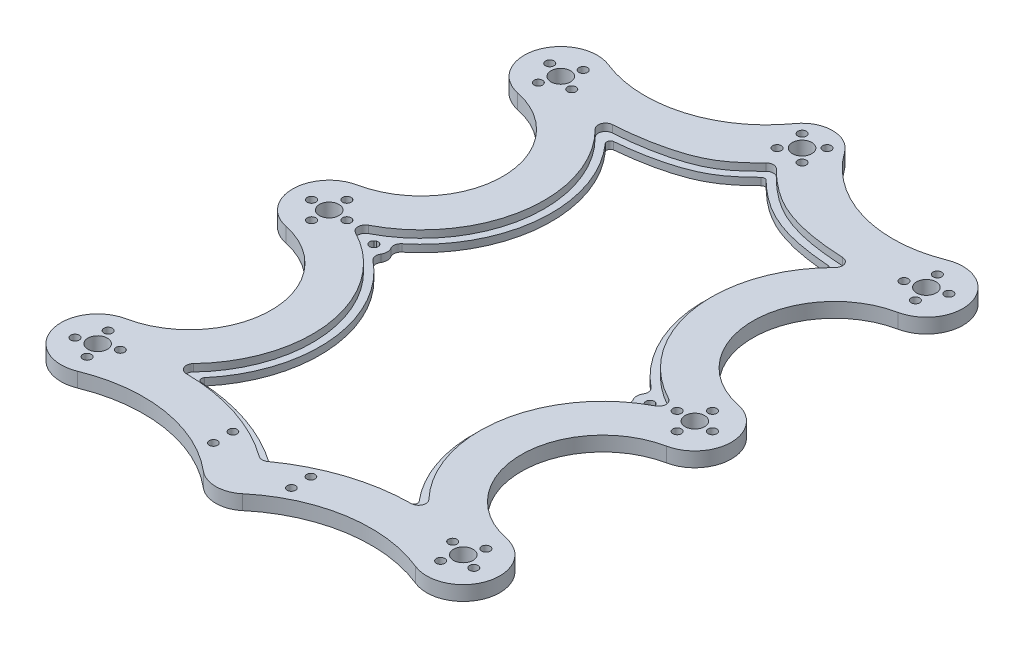
SolidWorks part; units mm, degrees
ref_plane "Front Plane" through (0, 0, 0) normal (0, 0, 1) x (1, 0, 0)
ref_plane "Top Plane" through (0, 0, 0) normal (0, 1, 0) x (1, 0, 0)
ref_plane "Right Plane" through (0, 0, 0) normal (1, 0, 0) x (0, 0, -1)
sketch "Sketch1" plane through (0, 0, 0) normal (0, 1, 0) x (1, 0, 0)
  line L0 (-75, 0) -> (75, 0) construction
  line L1 (-75, -95) -> (-75, -190) construction
  line L3 (0, 0) -> (0, -204) construction
  line L4 (0, 0) -> (0, 24)
  circle A0 centre (-75, 0) radius 15
  circle A1 centre (75, 0) radius 15
  circle A2 centre (-75, -95) radius 15
  circle A3 centre (75, -95) radius 15
  circle A4 centre (-75, -190) radius 15
  circle A5 centre (75, -190) radius 15
  circle A6 centre (-84.798, -142.5) radius 33.5
  circle A10 centre (0, -204) radius 12.5
  circle A11 centre (0, 24) radius 12.5
  circle A12 centre (-46.7001, -259.4559) radius 60
  circle A13 centre (46.7001, -259.4559) radius 60
  circle A14 centre (-50.8455, 60.3453) radius 50
  circle A15 centre (50.8455, 60.3453) radius 50
  circle A16 centre (84.798, -142.5) radius 33.5
  circle A17 centre (-84.798, -47.5) radius 33.5
  circle A18 centre (84.798, -47.5) radius 33.5
  dimension "D3" = 30
  dimension "D4" = 30
  dimension "D10" = 25
  dimension "D12" = 25
  dimension "D13" = 120
  dimension "D14" = 120
  dimension "D15" = 100
  dimension "D16" = 100
  dimension "D6" = 67
  dimension "D7" = 67
  dimension "D8" = 67
  dimension "D17" = 67
  dimension "D1" = 3
  dimension "D2" = 150
  dimension "D5" = 95
  dimension "D9" = 228
  dimension "D11" = 24
extrude "Boss-Extrude1" add sketch "Sketch1" along normal blind 6
sketch "Sketch2" plane through (0, 0, 0) normal (0, -1, 0) x (1, 0, 0)
  circle A0 centre (-75, 190) radius 4
  circle A1 centre (-75, 95) radius 4
  circle A2 centre (-75, 0) radius 4
  circle A3 centre (75, 0) radius 4
  circle A4 centre (75, 95) radius 4
  circle A5 centre (75, 190) radius 4
  circle A6 centre (0, -24) radius 4
  arc A8 (-10.1691, -31.2691) -> (10.1691, -31.2691) centre (0, -24) ccw construction
  dimension "D1" = 8
  dimension "D2" = 8
  dimension "D3" = 8
  dimension "D4" = 8
  dimension "D5" = 8
  dimension "D6" = 8
  dimension "D7" = 8
extrude "Cut-Extrude1" cut sketch "Sketch2" against normal through all
sketch "Sketch3" plane through (0, 6, 0) normal (0, 1, 0) x (1, 0, 0)
  line L0 (0, -216.5) -> (0, -189.6086) construction
  circle A0 centre (-16, -193.5) radius 1.7
  circle A1 centre (16, -193.5) radius 1.7
  circle A2 centre (-16, -201.5) radius 1.7
  circle A3 centre (16, -201.5) radius 1.7
  arc A4 (-8.0517, -213.5614) -> (8.0517, -213.5614) centre (0, -204) ccw construction
  point P15 (0, -216.5)
  dimension "D1" = 3.4
  dimension "D2" = 3.4
  dimension "D3" = 3.4
  dimension "D4" = 3.4
  dimension "D5" = 32
  dimension "D6" = 8
  dimension "D7" = 15
  dimension "D8" = 16
extrude "Cut-Extrude2" cut sketch "Sketch3" against normal up to next
sketch "Sketch4" plane through (0, 6, 0) normal (0, 1, 0) x (1, 0, 0)
  line L0 (-75, -95) -> (75, -95) construction
  line L1 (0, 0) -> (0, -6.5) construction
  circle A1 centre (0, 9.2337) radius 3
  arc A16 (48.2843, -177.3856) -> (46.1371, -182.4579) centre (46.1152, -179.458) cw
  arc A17 (-1.7513, -196.937) -> (1.7513, -196.937) centre (0, -194.5012) ccw
  arc A18 (-46.1371, -182.4579) -> (-48.2843, -177.3856) centre (-46.1152, -179.458) cw
  arc A19 (-61.5613, -92.3364) -> (-61.5613, -97.6636) centre (-60.1809, -95) ccw
  arc A20 (61.5613, -97.6636) -> (61.5613, -92.3364) centre (60.1809, -95) ccw
  arc A21 (49.1991, -11.6814) -> (47.2455, -6.5579) centre (47.0844, -9.5535) ccw
  arc A22 (2.1791, 14.2956) -> (-2.1791, 14.2956) centre (0, 12.2337) ccw
  arc A23 (-47.2455, -6.5579) -> (-49.1991, -11.6814) centre (-47.0844, -9.5535) ccw
  arc A32 (0, 16.7135) -> (55.3066, -6.506) centre (50.8455, 60.3453) ccw
  arc A33 (-55.3066, -6.506) -> (0, 16.7135) centre (-50.8455, 60.3453) ccw
  arc A34 (-67.6515, -95) -> (-55.3066, -6.506) centre (-84.798, -47.5) ccw
  arc A35 (-54.4237, -182.8442) -> (-67.6515, -95) centre (-84.798, -142.5) ccw
  arc A36 (0, -198.2341) -> (-54.4237, -182.8442) centre (-46.7001, -259.4559) ccw
  arc A37 (54.4237, -182.8442) -> (0, -198.2341) centre (46.7001, -259.4559) ccw
  arc A38 (67.6515, -95) -> (54.4237, -182.8442) centre (84.798, -142.5) ccw
  arc A39 (55.3066, -6.506) -> (67.6515, -95) centre (84.798, -47.5) ccw
  arc A40 (2.1791, 14.2956) -> (47.2455, -6.5579) centre (50.8455, 60.3453) ccw
  arc A41 (-47.2455, -6.5579) -> (-2.1791, 14.2956) centre (-50.8455, 60.3453) ccw
  arc A42 (-61.5613, -92.3364) -> (-49.1991, -11.6814) centre (-84.798, -47.5) ccw
  arc A43 (-48.2843, -177.3856) -> (-61.5613, -97.6636) centre (-84.798, -142.5) ccw
  arc A44 (-1.7513, -196.937) -> (-46.1371, -182.4579) centre (-46.7001, -259.4559) ccw
  arc A45 (46.1371, -182.4579) -> (1.7513, -196.937) centre (46.7001, -259.4559) ccw
  arc A46 (61.5613, -97.6636) -> (48.2843, -177.3856) centre (84.798, -142.5) ccw
  arc A47 (49.1991, -11.6814) -> (61.5613, -92.3364) centre (84.798, -47.5) ccw
  spline S0 degree 3 poles (-47.2455, -6.5579) (-40.9518, -6.2192) (-18.1874, -3.5989) (-6.8158, 6.6219) (-2.13, 11.3463) knots 0 0 0 0 0.623296 1 1 1 1
  spline S1 degree 3 poles (47.2455, -6.5579) (36.4418, -5.9765) (19.5152, -3.6368) (6.8583, 6.5791) (2.13, 11.3463) knots 0 0 0 0 0.623296 1 1 1 1
  point P24 (-75, 0)
  point P25 (-75, 0)
  point P26 (-75, -95)
  point P61 (-75, -95)
  dimension "D2" = 3
  dimension "D3" = 3
  dimension "D4" = 6
  dimension "D7" = 6.5
  dimension "D5" = 17
  dimension "D6" = 6.5
  dimension "D8" = 6.5
  dimension "D9" = 17
  dimension "D1" = 17
extrude "Cut-Extrude3" cut sketch "Sketch4" against normal blind 3 contours A21 S1 A1 S0 A23 A42 A19 A43 A18 A44 A17 A45 A16 A46 A20 A47 | A1
sketch "Sketch5" plane through (0, 3, 0) normal (0, 1, 0) x (1, 0, 0)
  arc A28 (-43.9741, -177.0783) -> (-42.9007, -179.5461) centre (-42.8295, -178.0478) ccw
  arc A30 (-0.8595, -193.8918) -> (0.8595, -193.8918) centre (0, -192.6625) ccw
  arc A32 (42.9007, -179.5461) -> (43.9741, -177.0783) centre (42.8295, -178.0478) ccw
  arc A33 (57.8278, -93.7045) -> (57.8278, -96.2955) centre (57.0716, -95) cw
  arc A34 (-57.8278, -93.7045) -> (-57.8278, -96.2955) centre (-57.0716, -95) ccw
  arc A35 (44.9062, -11.8503) -> (43.895, -9.3546) centre (43.7878, -10.8508) ccw
  arc A36 (1.0526, 8.1879) -> (-1.0523, 8.1814) centre (0.0034, 7.1158) ccw
  arc A37 (-43.9467, -9.3268) -> (-44.9322, -11.8213) centre (-43.8145, -10.8209) ccw
  arc A44 (-60.1809, -95) -> (-47.0844, -9.5535) centre (-84.798, -47.5) ccw
  arc A45 (-46.1152, -179.458) -> (-60.1809, -95) centre (-84.798, -142.5) ccw
  arc A46 (0, -194.5012) -> (-46.1152, -179.458) centre (-46.7001, -259.4559) ccw
  arc A47 (46.1152, -179.458) -> (0, -194.5012) centre (46.7001, -259.4559) ccw
  arc A63 (60.1809, -95) -> (46.1152, -179.458) centre (84.798, -142.5) ccw
  arc A64 (47.0844, -9.5535) -> (60.1809, -95) centre (84.798, -47.5) ccw
  arc A65 (-57.8278, -93.7045) -> (-44.9322, -11.8213) centre (-84.798, -47.5) ccw
  arc A66 (-43.9741, -177.0783) -> (-57.8278, -96.2955) centre (-84.798, -142.5) ccw
  arc A67 (-0.8595, -193.8918) -> (-42.9007, -179.5461) centre (-46.7001, -259.4559) ccw
  arc A68 (42.9007, -179.5461) -> (0.8595, -193.8918) centre (46.7001, -259.4559) ccw
  arc A69 (57.8278, -96.2955) -> (43.9741, -177.0783) centre (84.798, -142.5) ccw
  arc A70 (44.9062, -11.8503) -> (57.8278, -93.7045) centre (84.798, -47.5) ccw
  spline S4 degree 3 poles (100.0873, -2995.8706) (300.1665, 192.4496) (155.0404, -27.22) (33.0075, -8.1036) (31.9339, -7.9158) (29.8041, -7.4985) (28.7465, -7.2687) (25.5987, -6.5079) (23.5332, -5.9057) (19.4851, -4.4639) (17.5023, -3.6245) (14.6046, -2.1457) (13.6515, -1.6162) (12.2404, -0.7684) (11.7734, -0.477) (10.8523, 0.1184) (10.3973, 0.423) (-79.8726, 62.8565) (39.1163, 380.7981) (-2122.6541, -2095.4949) knots -6.768961 -6.768961 -6.768961 -6.768961 0.25 0.25 0.3125 0.3125 0.375 0.375 0.5 0.5 0.625 0.625 0.6875 0.6875 0.71875 0.71875 0.75 0.75 6.991805 6.991805 6.991805 6.991805 only from (47.0844, -9.5535) to (0, 9.2337)
  spline S5 degree 3 poles (2022.5302, -2198.8508) (29.0809, 220.8369) (55.0884, 57.9301) (-6.31, 3.3026) (-7.9878, 1.9482) (-10.6529, 0.1061) (-11.5657, -0.4767) (-12.9754, -1.299) (-13.452, -1.5645) (-14.4191, -2.0778) (-14.91, -2.3258) (-17.3759, -3.5103) (-19.401, -4.2913) (-23.5145, -5.652) (-25.6036, -6.2295) (-28.7715, -6.9867) (-29.8333, -7.2205) (-31.9672, -7.6555) (-33.0397, -7.8566) (-36.2602, -8.4134) (-38.4147, -8.7241) (-41.657, -9.1057) (-42.7396, -9.2187) (-119.2361, -16.069) (-203.8006, 50.5894) (-638.6374, 2926.7332) knots -4.505037 -4.505037 -4.505037 -4.505037 0.125 0.125 0.25 0.25 0.3125 0.3125 0.34375 0.34375 0.375 0.375 0.5 0.5 0.625 0.625 0.6875 0.6875 0.75 0.75 0.875 0.875 0.9375 0.9375 5.283411 5.283411 5.283411 5.283411 only from (0, 9.2337) to (-47.0844, -9.5535)
  spline S6 degree 3 poles (43.895, -9.3546) (40.6121, -9.1193) (37.3396, -8.7822) (33.0075, -8.1036) (31.9339, -7.9158) (29.8041, -7.4985) (28.7465, -7.2687) (25.5987, -6.5079) (23.5332, -5.9057) (19.4851, -4.4639) (17.5023, -3.6245) (14.6046, -2.1457) (13.6515, -1.6162) (12.2404, -0.7684) (11.7734, -0.477) (10.8523, 0.1184) (10.3973, 0.423) (6.7562, 2.9413) (3.8284, 5.4715) (1.0526, 8.1879) knots 0.061111 0.061111 0.061111 0.061111 0.25 0.25 0.3125 0.3125 0.375 0.375 0.5 0.5 0.625 0.625 0.6875 0.6875 0.71875 0.71875 0.75 0.75 0.971778 0.971778 0.971778 0.971778
  spline S7 degree 3 poles (-1.0523, 8.1814) (-2.2423, 7.0024) (-3.4505, 5.8467) (-6.31, 3.3026) (-7.9878, 1.9482) (-10.6529, 0.1061) (-11.5657, -0.4767) (-12.9754, -1.299) (-13.452, -1.5645) (-14.4191, -2.0778) (-14.91, -2.3258) (-17.3759, -3.5103) (-19.401, -4.2913) (-23.5145, -5.652) (-25.6036, -6.2295) (-28.7715, -6.9867) (-29.8333, -7.2205) (-31.9672, -7.6555) (-33.0397, -7.8566) (-36.2602, -8.4134) (-38.4147, -8.7241) (-41.657, -9.1057) (-42.7396, -9.2187) (-43.8649, -9.3195) (-43.9058, -9.3232) (-43.9467, -9.3268) knots 0.028546 0.028546 0.028546 0.028546 0.125 0.125 0.25 0.25 0.3125 0.3125 0.34375 0.34375 0.375 0.375 0.5 0.5 0.625 0.625 0.6875 0.6875 0.75 0.75 0.875 0.875 0.9375 0.9375 0.939854 0.939854 0.939854 0.939854
  dimension "D2" = 1.5
  dimension "D1" = 3
extrude "Cut-Extrude4" cut sketch "Sketch5" against normal up to next contours A36 S7 A37 A65 A34 A66 A28 A67 A30 A68 A32 A69 A33 A70 A35 S6
sketch "Sketch6" plane through (0, 6, 0) normal (0, 1, 0) x (1, 0, 0)
  line L0 (-46.1152, -179.458) -> (-75, -190) construction
  line L1 (-47.0844, -9.5535) -> (-75, 0) construction
  line L2 (0, 0) -> (0, -13.1592) construction
  line L3 (47.0844, -9.5535) -> (75, 0) construction
  line L4 (46.1152, -179.458) -> (75, -190) construction
  line L5 (-75, -95) -> (75, -95) construction
  circle A0 centre (-68.1894, -187.5144) radius 1.75
  circle A1 centre (-72.5144, -196.8106) radius 1.75
  circle A2 centre (-81.8106, -192.4856) radius 1.75
  circle A3 centre (-77.4856, -183.1894) radius 1.75
  circle A4 centre (-75, -87.75) radius 1.75
  circle A5 centre (-75, -95) radius 4 construction
  circle A6 centre (-67.75, -95) radius 1.75
  circle A7 centre (-75, -102.25) radius 1.75
  circle A8 centre (-82.25, -95) radius 1.75
  circle A9 centre (-68.1406, -2.3475) radius 1.75
  circle A10 centre (-77.3475, -6.8594) radius 1.75
  circle A11 centre (-81.8594, 2.3475) radius 1.75
  circle A12 centre (-72.6525, 6.8594) radius 1.75
  circle A13 centre (72.6525, 6.8594) radius 1.75
  circle A14 centre (81.8594, 2.3475) radius 1.75
  circle A15 centre (77.3475, -6.8594) radius 1.75
  circle A16 centre (68.1406, -2.3475) radius 1.75
  circle A17 centre (82.25, -95) radius 1.75
  circle A18 centre (75, -102.25) radius 1.75
  circle A19 centre (67.75, -95) radius 1.75
  circle A20 centre (75, -87.75) radius 1.75
  circle A21 centre (77.4856, -183.1894) radius 1.75
  circle A22 centre (81.8106, -192.4856) radius 1.75
  circle A23 centre (72.5144, -196.8106) radius 1.75
  circle A24 centre (68.1894, -187.5144) radius 1.75
  point P15 (-75, -190)
  point P26 (-75, -95)
  point P39 (-75, 0)
  point P68 (75, -95)
  dimension "D1" = 3.5
  dimension "D3" = 3.5
  dimension "D4" = 7.25
  dimension "D5" = 3.5
  dimension "D2" = 7.25
  dimension "D6" = 7.25
extrude "Cut-Extrude5" cut sketch "Sketch6" against normal up to next
sketch "Sketch8" plane through (0, 6, 0) normal (0, 1, 0) x (1, 0, 0)
  circle A0 centre (-5.1265, 29.1265) radius 1.75
  circle A1 centre (0, 24) radius 4 construction
  circle A2 centre (5.1265, 29.1265) radius 1.75
  circle A3 centre (5.1265, 18.8735) radius 1.75
  circle A4 centre (-5.1265, 18.8735) radius 1.75
  point P13 (0, 24)
  dimension "D1" = 3.5
  dimension "D2" = 7.25
extrude "Cut-Extrude6" cut sketch "Sketch8" against normal up to next
sketch "Sketch9" plane through (0, 3, 0) normal (0, 1, 0) x (1, 0, 0)
  line L0 (-75, -95) -> (75, -95) construction
  circle A0 centre (-55.1809, -95) radius 4
  circle A1 centre (-56.6809, -95) radius 1.75
  arc A2 (-61.5613, -92.3364) -> (-61.5613, -97.6636) centre (-60.1809, -95) ccw construction
  circle A3 centre (55.1809, -95) radius 4
  arc A4 (-61.5613, -92.3364) -> (-61.5613, -97.6636) centre (-60.1809, -95) ccw construction
  arc A5 (61.5613, -97.6636) -> (61.5613, -92.3364) centre (60.1809, -95) ccw construction
  circle A6 centre (56.6809, -95) radius 1.75
  arc A7 (61.5613, -97.6636) -> (61.5613, -92.3364) centre (60.1809, -95) ccw construction
  dimension "D1" = 8
  dimension "D2" = 3.5
  dimension "D4" = 8
  dimension "D5" = 5
  dimension "D6" = 5
  dimension "D7" = 3.5
  dimension "D3" = 3.5
  dimension "D8" = 3.5
extrude "Boss-Extrude2" add sketch "Sketch9" against normal through all
fillet "Fillet1" radius 3 4 edges at (53.9336, 1.5, 98.8006) (53.9336, 1.5, 91.1994) (-53.9336, 1.5, 98.8006) (-53.9336, 1.5, 91.1994)
